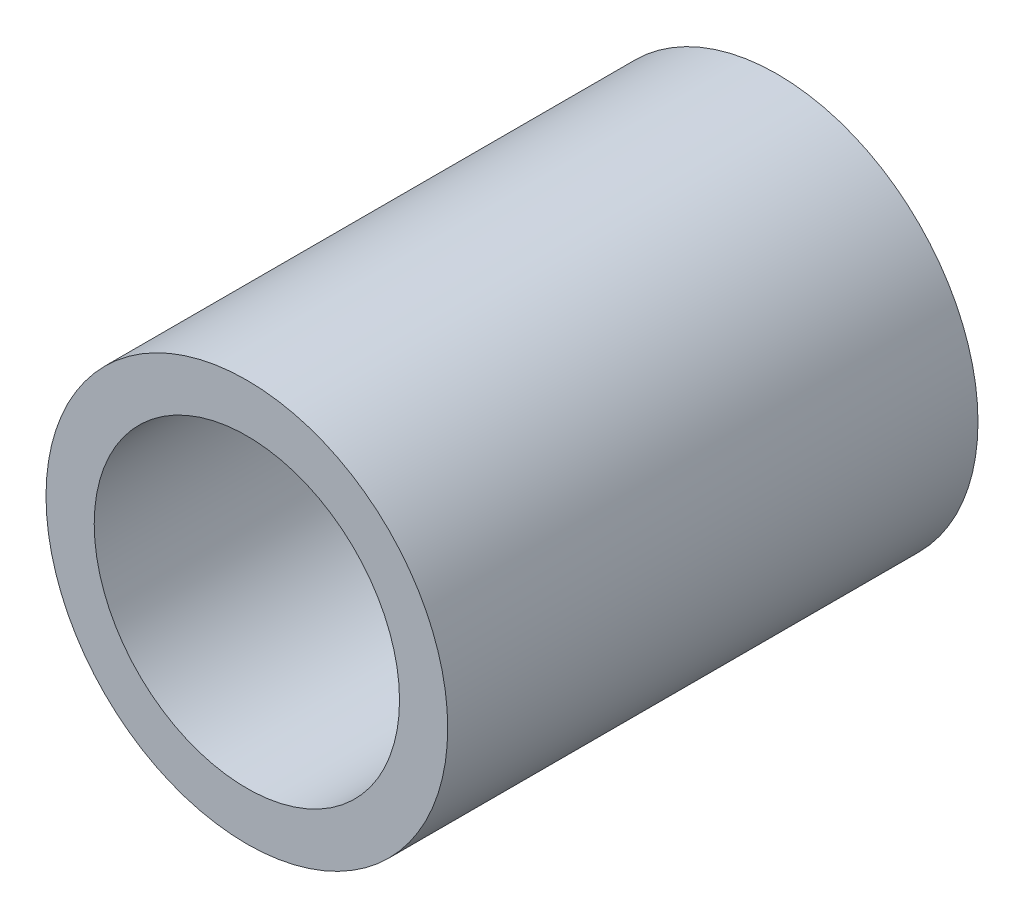
SolidWorks part; units mm, degrees
material "6061 合金"
ref_plane "前视基准面" through (0, 0, 0) normal (0, 0, 1) x (1, 0, 0)
ref_plane "上视基准面" through (0, 0, 0) normal (0, 1, 0) x (1, 0, 0)
ref_plane "右视基准面" through (0, 0, 0) normal (1, 0, 0) x (0, 0, -1)
sketch "草图1" plane through (0, 0, 0) normal (0, 0, 1) x (1, 0, 0)
  circle A0 centre (0, 0) radius 2.5
  circle A1 centre (0, 0) radius 1.9
  dimension "D1" = 5
  dimension "D2" = 3.8
extrude "凸台-拉伸1" add sketch "草图1" along normal blind 6.6
